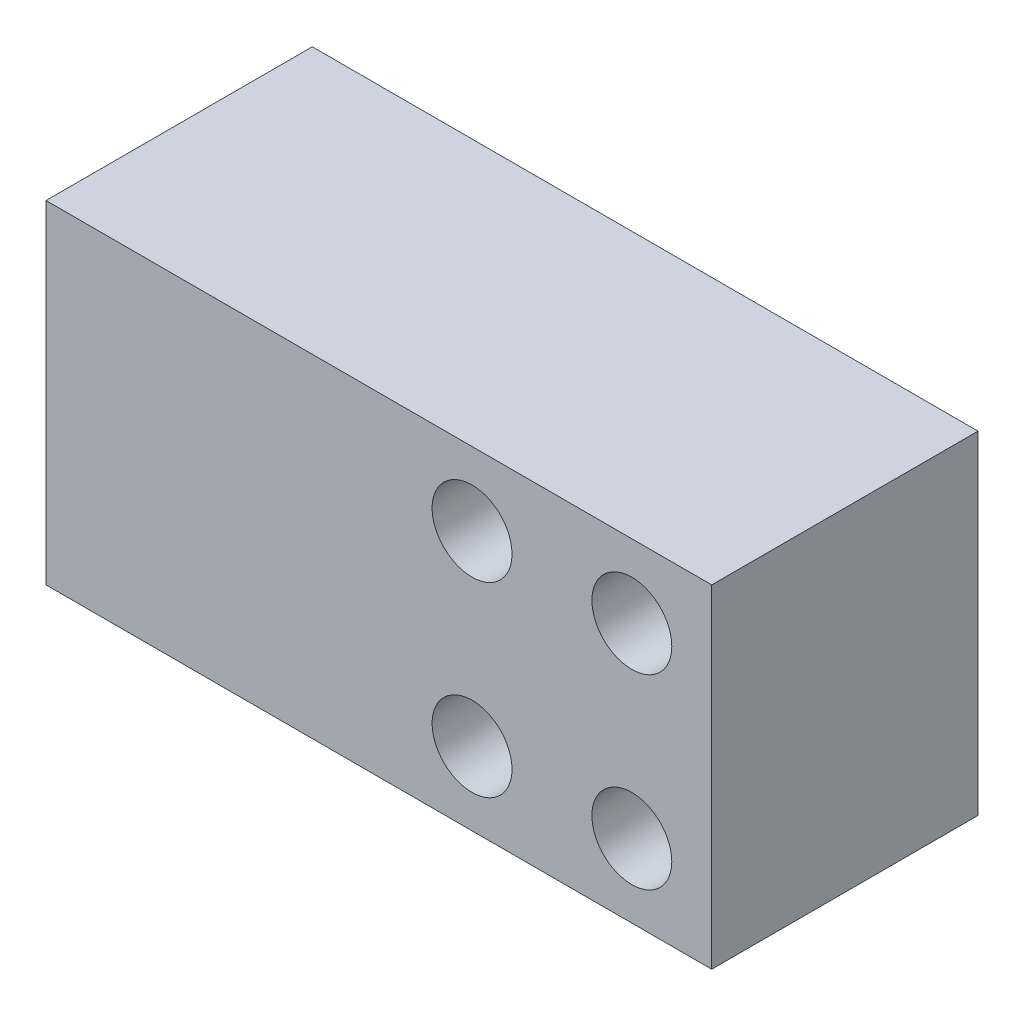
SolidWorks part; units mm, degrees
ref_plane "前视基准面" through (0, 0, 0) normal (0, 0, 1) x (1, 0, 0)
ref_plane "上视基准面" through (0, 0, 0) normal (0, 1, 0) x (1, 0, 0)
ref_plane "右视基准面" through (0, 0, 0) normal (1, 0, 0) x (0, 0, -1)
other "Configuration Table"
sketch "草图1" plane through (0, 0, 0) normal (0, 0, 1) x (1, 0, 0)
  line L1 (0, 0) -> (50, 0)
  line L2 (0, 0) -> (0, -25)
  line L3 (0, -25) -> (50, -25)
  line L4 (50, 0) -> (50, -25)
  dimension "D1" = 25
  dimension "D2" = 50
extrude "凸台-拉伸1" add sketch "草图1" along normal blind 20
sketch "草图2" plane through (0, 0, 20) normal (0, 0, 1) x (1, 0, 0)
  line L0 (50, -25) -> (50, 0) construction
  line L1 (50, -12.5) -> (18.8213, -12.5) construction
  circle A0 centre (44, -5.5) radius 3
  circle A1 centre (32, -5.5) radius 3
  circle A2 centre (32, -19.5) radius 3
  circle A3 centre (44, -19.5) radius 3
  dimension "D1" = 6
  dimension "D2" = 6
  dimension "D4" = 14
  dimension "D3" = 2
extrude "切除-拉伸1" cut sketch "草图2" against normal blind 45
